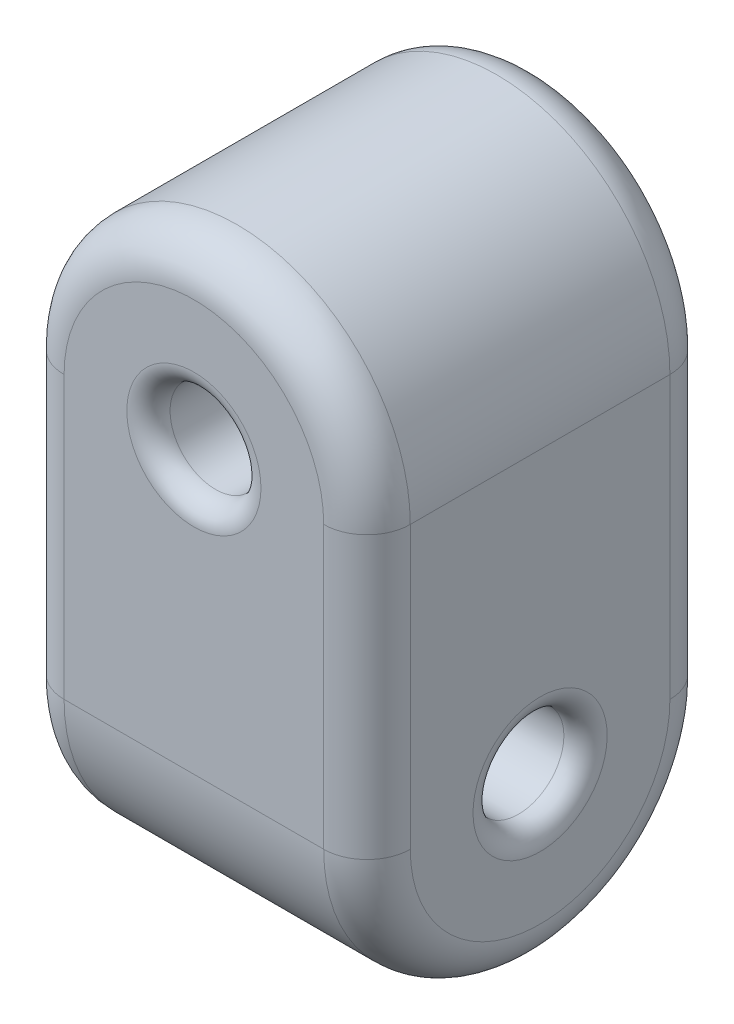
SolidWorks part; units mm, degrees
ref_plane "Front Plane" through (0, 0, 0) normal (0, 0, 1) x (1, 0, 0)
ref_plane "Top Plane" through (0, 0, 0) normal (0, 1, 0) x (1, 0, 0)
ref_plane "Right Plane" through (0, 0, 0) normal (1, 0, 0) x (0, 0, -1)
sketch "Sketch1" plane through (0, 0, 0) normal (0, 0, 1) x (1, 0, 0)
  circle A0 centre (0, 0) radius 1.05
sketch "Sketch2" plane through (0, 0, 0) normal (0, 0, 1) x (1, 0, 0)
  circle A0 centre (0, 0) radius 4
extrude "Boss-Extrude1" add sketch "Sketch2" along normal blind 8 from offset 0.8
sketch "Sketch7" plane through (0, 0, 0.8) normal (0, 0, -1) x (-1, 0, 0)
  line L0 (0, 0) -> (0, -18) construction
  dimension "D1" = 18
sketch "Sketch8" plane through (0, 0, 0) normal (1, 0, 0) x (0, 0, -1)
  circle A0 centre (-4.8, -6.5) radius 4
  dimension "D1" = 6.5
sketch "Sketch9" plane through (0, 0, 0) normal (1, 0, 0) x (0, 0, -1)
  circle A0 centre (-4.8, -6.5) radius 1.05
  dimension "D1" = 6.5
sketch "Sketch10" plane through (0, 0, 0.8) normal (0, 0, -1) x (-1, 0, 0)
  line L1 (-4, 0) -> (4, 0)
  line L2 (-4, 0) -> (-4, -6.5)
  line L3 (-4, -6.5) -> (4, -6.5)
  line L4 (4, 0) -> (4, -6.5)
  circle A0 centre (0, 0) radius 4 construction
  dimension "D1" = 6.5
extrude "Boss-Extrude2" add sketch "Sketch10" against normal blind 8 contours L4 L3 L2 L1
extrude "Boss-Extrude3" add sketch "Sketch8" against normal blind 8 from offset 4 contours A0
extrude "Cut-Extrude2" cut sketch "Sketch1" along normal blind 9.6 contours A0
extrude "Cut-Extrude3" cut sketch "Sketch9" against normal blind 9.95 from offset 4.975
fillet "Fillet1" radius 1 8 edges at (4, -3.25, 8.8) (4, -3.25, 0.8) (4, -10.5, 4.8) (-4, -3.25, 0.8) (-4, -3.25, 8.8) (-4, -10.5, 4.8) (0, 4, 8.8) (0, 4, 0.8)
fillet "Fillet2" radius 0.5 4 edges at (1.05, 0, 8.8) (1.05, 0, 0.8) (-4, -5.45, 4.8) (4, -5.45, 4.8)
